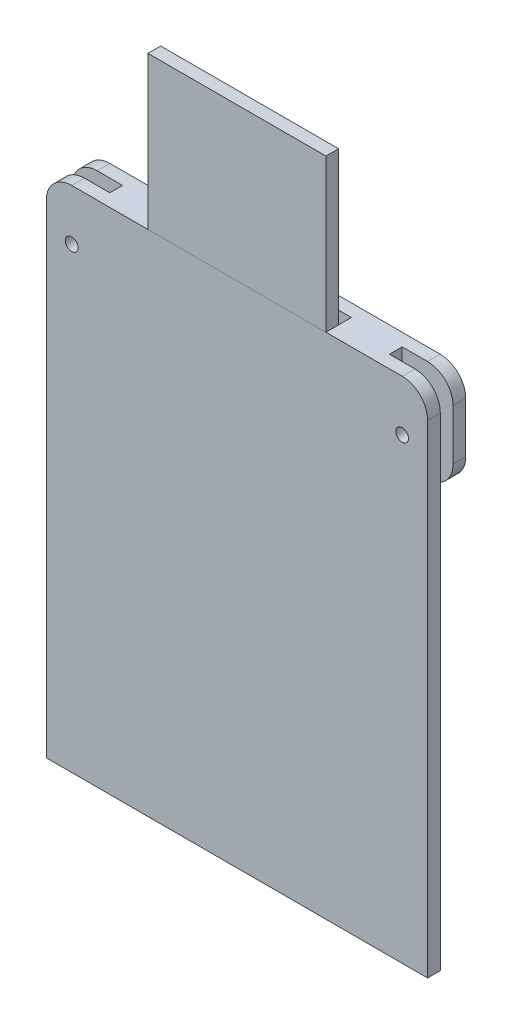
SolidWorks part; units mm, degrees
ref_plane "Front Plane" through (0, 0, 0) normal (0, 0, 1) x (1, 0, 0)
ref_plane "Top Plane" through (0, 0, 0) normal (0, 1, 0) x (1, 0, 0)
ref_plane "Right Plane" through (0, 0, 0) normal (1, 0, 0) x (0, 0, -1)
sketch "Sketch2" plane through (0, 0, 0) normal (0, 0, 1) x (1, 0, 0)
  line L1 (-70.2157, 39.5009) -> (79.7843, 39.5009)
  line L2 (-70.2157, 39.5009) -> (-70.2157, -160.4991)
  line L3 (-70.2157, -160.4991) -> (79.7843, -160.4991)
  line L4 (79.7843, 39.5009) -> (79.7843, -160.4991)
  dimension "D1" = 150
  dimension "D2" = 200
extrude "Boss-Extrude1" add sketch "Sketch2" along normal blind 5
sketch "Sketch3" plane through (0, 0, 0) normal (0, 0, -1) x (-1, 0, 0)
  line L0 (-79.7843, 39.5009) -> (-79.7843, 19.5009)
  line L1 (-79.7843, -160.4991) -> (-79.7843, 39.5009) construction
  line L2 (-79.7843, 19.5009) -> (-79.7843, -10.4991)
  line L3 (-79.7843, -10.4991) -> (-79.7843, -30.4991)
  dimension "D1" = 20
  dimension "D2" = 30
sketch "Sketch4" plane through (0, 0, 0) normal (0, 0, -1) x (-1, 0, 0)
  line L0 (-79.7843, 39.5009) -> (-59.7843, 39.5009)
  line L1 (-79.7843, 39.5009) -> (70.2157, 39.5009) construction
  line L2 (-59.7843, 39.5009) -> (50.2157, 39.5009)
  line L3 (50.2157, 39.5009) -> (70.2157, 39.5009)
  line L5 (-59.7843, 39.5009) -> (-39.7843, 39.5009)
  line L6 (-59.7843, 39.5009) -> (-59.7843, -0.4991)
  line L7 (-59.7843, -0.4991) -> (-39.7843, -0.4991)
  line L8 (-39.7843, 39.5009) -> (-39.7843, -0.4991)
  line L9 (50.2157, 39.5009) -> (30.2157, 39.5009)
  line L10 (50.2157, 39.5009) -> (50.2157, -0.4991)
  line L11 (50.2157, -0.4991) -> (30.2157, -0.4991)
  line L12 (30.2157, 39.5009) -> (30.2157, -0.4991)
  line M2 (70.2157, 39.5009) -> (-79.7843, 39.5009)
  dimension "D1" = 20
  dimension "D2" = 20
  dimension "D3" = 20
  dimension "D4" = 20
  dimension "D5" = 40
  dimension "D6" = 40
extrude "Boss-Extrude2" add sketch "Sketch4" along normal blind 5 contours L8 L2 L6 L7 | L12 L11 L10 M2
sketch "Sketch6" plane through (0, 0, -5) normal (0, 0, -1) x (-1, 0, 0)
  line L0 (70.2157, 39.5009) -> (70.2157, -160.4991) construction
  line L1 (-79.7843, 39.5009) -> (70.2157, 39.5009)
  line L2 (-79.7843, 39.5009) -> (-79.7843, -0.4991)
  line L3 (-79.7843, -0.4991) -> (70.2157, -0.4991)
  line L4 (70.2157, 39.5009) -> (70.2157, -0.4991)
  dimension "D1" = 40
extrude "Boss-Extrude3" add sketch "Sketch6" along normal blind 5
sketch "Sketch7" plane through (0, 0, 0) normal (0, 0, -1) x (-1, 0, 0)
  line L0 (70.2157, 39.5009) -> (70.2157, -0.4991)
  line L1 (70.2157, 39.5009) -> (70.2157, -160.4991) construction
  line L2 (70.2157, -0.4991) -> (-79.7843, -0.4991)
  line L3 (-79.7843, 19.5009) -> (-79.7843, -10.4991) construction
  line L4 (-79.7843, -0.4991) -> (-79.7843, 39.5009)
  line L5 (-79.7843, 39.5009) -> (-59.7843, 39.5009)
  line L6 (-79.7843, 39.5009) -> (70.2157, 39.5009) construction
  line L7 (-79.7843, 39.5009) -> (-59.7843, 39.5009) construction
  line L8 (-59.7843, 39.5009) -> (50.2157, 39.5009)
  line L9 (50.2157, 39.5009) -> (70.2157, 39.5009) construction
  line L10 (50.2157, 39.5009) -> (70.2157, 39.5009)
  line L11 (-79.7843, -0.4991) -> (-59.7843, 39.5009)
  line L12 (50.2157, 39.5009) -> (70.2157, -0.4991)
  circle A0 centre (-69.7843, 19.5009) radius 2.5
  circle A1 centre (60.2157, 19.5009) radius 2.5
  dimension "D4" = 5
  dimension "D5" = 5
  dimension "D1" = 40
  dimension "D2" = 20
  dimension "D3" = 20
extrude "Cut-Extrude1" cut sketch "Sketch7" against normal through all and the other way through all contours A0 | A1
sketch "Sketch8" plane through (0, 0, -10) normal (0, 0, -1) x (-1, 0, 0)
  line L0 (-69.7843, 19.5009) -> (60.2157, 19.5009)
fillet "Fillet1" radius 10 1 edges at (-70.2157, 39.5009, -7.5)
fillet "Fillet2" radius 10 1 edges at (-70.2157, 39.5009, 2.5)
fillet "Fillet3" radius 10 2 edges at (79.7843, 39.5009, 2.5)
fillet "Fillet4" radius 10 1 edges at (79.7843, 39.5009, -7.5)
fillet "Fillet5" radius 10 1 edges at (79.7843, -0.4991, -7.5)
fillet "Fillet6" radius 10 1 edges at (-70.2157, -0.4991, -7.5)
sketch "Sketch9" plane through (0, 0, 0) normal (0, 0, -1) x (-1, 0, 0)
  line L0 (-69.7843, 19.5009) -> (60.2157, 19.5009)
  line L1 (-4.7843, 19.5009) -> (-4.7843, -40.4991)
  line L3 (-10.7843, -33.4991) -> (1.2157, -33.4991)
  line L4 (-10.7843, -33.4991) -> (-10.7843, -55.4991)
  line L5 (-10.7843, -55.4991) -> (1.2157, -55.4991)
  line L6 (1.2157, -33.4991) -> (1.2157, -55.4991)
  dimension "D1" = 60
  dimension "D2" = 22
  dimension "D3" = 12
  dimension "D4" = 6
  dimension "D5" = 7
extrude "Boss-Extrude4" add sketch "Sketch9" along normal blind 23
sketch "Sketch10" plane through (0, 0, -23) normal (0, 0, -1) x (-1, 0, 0)
  line L0 (-4.7843, -33.4991) -> (-4.7843, -40.4991)
  line L1 (-10.7843, -33.4991) -> (1.2157, -33.4991) construction
  circle A0 centre (-4.7843, -40.4991) radius 6
  dimension "D2" = 12
  dimension "D1" = 7
extrude "Boss-Extrude5" add sketch "Sketch10" along normal blind 4
sketch "Sketch11" plane through (0, 0, -27) normal (0, 0, -1) x (-1, 0, 0)
  circle A0 centre (-4.7843, -40.4991) radius 2
  dimension "D1" = 4
extrude "Boss-Extrude6" add sketch "Sketch11" along normal blind 3
sketch "Sketch12" plane through (0, 0, 0) normal (0, 0, -1) x (-1, 0, 0)
  line L0 (-10.7843, -33.4991) -> (-10.7843, -40.4991) construction
  line L1 (-10.7843, -18.4991) -> (-15.7843, -18.4991)
  line L2 (-10.7843, -18.4991) -> (-10.7843, -68.4991)
  line L3 (-10.7843, -68.4991) -> (-15.7843, -68.4991)
  line L4 (-15.7843, -18.4991) -> (-15.7843, -68.4991)
  line L5 (1.2157, -68.4991) -> (6.2157, -68.4991)
  line L6 (1.2157, -68.4991) -> (1.2157, -18.4991)
  line L7 (1.2157, -18.4991) -> (6.2157, -18.4991)
  line L8 (6.2157, -68.4991) -> (6.2157, -18.4991)
  line L9 (-10.7843, -33.4991) -> (1.2157, -33.4991) construction
  dimension "D1" = 5
  dimension "D2" = 5
  dimension "D3" = 0
  dimension "D4" = 50
  dimension "D5" = 50
  dimension "D6" = 15
  dimension "D7" = 15
extrude "Boss-Extrude7" add sketch "Sketch12" along normal blind 15
sketch "Sketch13" plane through (0, 0, -15) normal (0, 0, -1) x (-1, 0, 0)
  line L0 (1.2157, -18.4991) -> (1.2157, -33.4991) construction
  line L1 (-10.7843, -33.4991) -> (1.2157, -33.4991)
  line L2 (-10.7843, -33.4991) -> (-10.7843, -28.4991)
  line L3 (-10.7843, -28.4991) -> (1.2157, -28.4991)
  line L4 (1.2157, -33.4991) -> (1.2157, -28.4991)
  line L5 (1.2157, -55.4991) -> (1.2157, -68.4991) construction
  line L6 (-10.7843, -55.4991) -> (1.2157, -55.4991)
  line L7 (-10.7843, -55.4991) -> (-10.7843, -60.4991)
  line L8 (-10.7843, -60.4991) -> (1.2157, -60.4991)
  line L9 (1.2157, -55.4991) -> (1.2157, -60.4991)
  dimension "D1" = 5
  dimension "D2" = 5
extrude "Boss-Extrude10" add sketch "Sketch13" against normal blind 15 separate body
sketch "Sketch14" plane through (0, 0, 0) normal (0, 0, -1) x (-1, 0, 0)
  line L0 (-69.7843, 19.5009) -> (60.2157, 19.5009)
  line L1 (60.2157, 19.5009) -> (-4.7843, 19.5009)
  line L2 (-4.7843, 19.5009) -> (-4.7843, -40.4991)
sketch "Sketch15" plane through (0, 39.5009, 0) normal (0, 1, 0) x (1, 0, 0)
  line L0 (-60.2157, 10) -> (69.7843, 10) construction
  line L1 (-30.2157, 10) -> (39.7843, 10)
  line L2 (-30.2157, 10) -> (-30.2157, -5)
  line L3 (-30.2157, -5) -> (39.7843, -5)
  line L4 (39.7843, 10) -> (39.7843, -5)
  line L5 (69.7843, -5) -> (-60.2157, -5) construction
extrude "Boss-Extrude11" add sketch "Sketch15" along normal blind 60 separate body
sketch "Sketch16" plane through (0, 99.5009, 0) normal (0, 1, 0) x (1, 0, 0)
  line L1 (-30.2157, 10) -> (39.7843, 10)
  line L2 (-30.2157, 10) -> (-30.2157, 0)
  line L3 (-30.2157, 0) -> (39.7843, 0)
  line L4 (39.7843, 10) -> (39.7843, 0)
extrude "Cut-Extrude2" cut sketch "Sketch16" against normal blind 60
